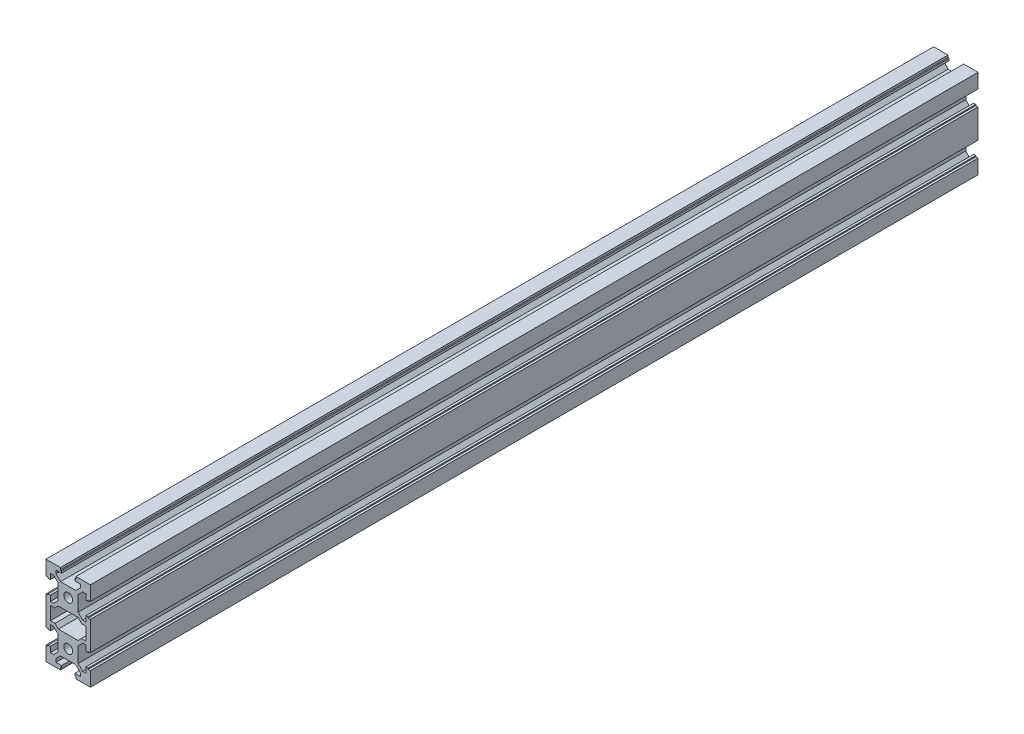
SolidWorks part; units mm, degrees
ref_plane "Front Plane" through (0, 0, 0) normal (0, 0, 1) x (1, 0, 0)
ref_plane "Top Plane" through (0, 0, 0) normal (0, 1, 0) x (1, 0, 0)
ref_plane "Right Plane" through (0, 0, 0) normal (1, 0, 0) x (0, 0, -1)
sketch "Sketch1" plane through (0, 0, 0) normal (0, 0, 1) x (1, 0, 0)
  line L0 (-10, 0) -> (10, 0) construction
  line L1 (-10, -20) -> (-3.5, -20)
  line L2 (-10, -20) -> (-10, -13.5)
  line L3 (-10, 20) -> (-3.5, 20)
  line L4 (10, -20) -> (10, -13.5)
  line L5 (-10, -20) -> (10, 20) construction
  line L6 (-10, 20) -> (10, -20) construction
  line L7 (-10, 20) -> (10, 0) construction
  line L8 (10, 20) -> (-10, 0) construction
  line L9 (-3.5, 20) -> (-3.5, 19)
  line L11 (-4.5007, 6.56) -> (-4.5007, 13.44)
  line L12 (-3.44, 14.5007) -> (3.44, 14.5007)
  line L13 (4.5007, 6.56) -> (4.5007, 13.44)
  line L14 (0, 20) -> (0, 10) construction
  line L15 (-10, 20) -> (10, 0) construction
  line L16 (-3.5, 19) -> (-3, 19)
  line L17 (-3, 19) -> (-3, 18)
  line L18 (-3, 18) -> (-5.5, 18)
  line L19 (-5.5, 18) -> (-5.5, 16.5607)
  line L20 (-5.5, 16.5607) -> (-3.44, 14.5007)
  line L21 (0, 20) -> (0, 10) construction
  line L22 (5.5, 16.5607) -> (3.44, 14.5007)
  line L23 (5.5, 18) -> (5.5, 16.5607)
  line L24 (3, 18) -> (5.5, 18)
  line L25 (3, 19) -> (3, 18)
  line L26 (3.5, 19) -> (3, 19)
  line L27 (3.5, 20) -> (3.5, 19)
  line L28 (3.5, 20) -> (10, 20)
  line L29 (-3.5, 20) -> (3.5, 20) construction
  line L30 (-9, 13.5) -> (-9, 13)
  line L31 (-6.5607, 15.5) -> (-4.5007, 13.44)
  line L32 (-8, 15.5) -> (-6.5607, 15.5)
  line L33 (-8, 13) -> (-8, 15.5)
  line L34 (-10, 13.5) -> (-9, 13.5)
  line L35 (-9, 13) -> (-8, 13)
  line L36 (10, 13.5) -> (9, 13.5)
  line L37 (9, 13.5) -> (9, 13)
  line L38 (9, 13) -> (8, 13)
  line L39 (8, 13) -> (8, 15.5)
  line L40 (8, 15.5) -> (6.5607, 15.5)
  line L41 (6.5607, 15.5) -> (4.5007, 13.44)
  line L42 (0, 10) -> (-10, 10) construction
  line L43 (10, 6.5) -> (9, 6.5)
  line L44 (9, 6.5) -> (9, 7)
  line L45 (9, 7) -> (8, 7)
  line L46 (8, 7) -> (8, 4.5)
  line L47 (8, 4.5) -> (6.5607, 4.5)
  line L48 (6.5607, 4.5) -> (4.5007, 6.56)
  line L49 (-6.5607, 4.5) -> (-4.5007, 6.56)
  line L50 (-8, 4.5) -> (-6.5607, 4.5)
  line L51 (-8, 7) -> (-8, 4.5)
  line L52 (-9, 6.5) -> (-9, 7)
  line L53 (-9, 7) -> (-8, 7)
  line L54 (-10, 6.5) -> (-9, 6.5)
  line L55 (4.5007, -6.56) -> (4.5007, -13.44)
  line L56 (-4.5007, -6.56) -> (-4.5007, -13.44)
  line L58 (-3.44, -14.5007) -> (3.44, -14.5007)
  line L59 (10, -13.5) -> (9, -13.5)
  line L60 (9, -13.5) -> (9, -13)
  line L61 (9, -13) -> (8, -13)
  line L62 (8, -13) -> (8, -15.5)
  line L63 (8, -15.5) -> (6.5607, -15.5)
  line L64 (6.5607, -15.5) -> (4.5007, -13.44)
  line L65 (6.5607, -4.5) -> (4.5007, -6.56)
  line L66 (8, -4.5) -> (6.5607, -4.5)
  line L67 (9, -6.5) -> (9, -7)
  line L68 (8, -7) -> (8, -4.5)
  line L69 (9, -7) -> (8, -7)
  line L70 (10, -6.5) -> (9, -6.5)
  line L71 (-10, -6.5) -> (-9, -6.5)
  line L72 (-8, -7) -> (-8, -4.5)
  line L73 (-6.5607, -4.5) -> (-4.5007, -6.56)
  line L74 (-8, -4.5) -> (-6.5607, -4.5)
  line L75 (-9, -7) -> (-8, -7)
  line L76 (-9, -6.5) -> (-9, -7)
  line L77 (-10, -13.5) -> (-9, -13.5)
  line L78 (-9, -13.5) -> (-9, -13)
  line L79 (-9, -13) -> (-8, -13)
  line L80 (-8, -13) -> (-8, -15.5)
  line L81 (-8, -15.5) -> (-6.5607, -15.5)
  line L82 (-6.5607, -15.5) -> (-4.5007, -13.44)
  line L83 (5.5, -16.5607) -> (3.44, -14.5007)
  line L84 (5.5, -18) -> (5.5, -16.5607)
  line L85 (3, -18) -> (5.5, -18)
  line L86 (3, -19) -> (3, -18)
  line L87 (3.5, -19) -> (3, -19)
  line L88 (3.5, -20) -> (3.5, -19)
  line L89 (-5.5, -16.5607) -> (-3.44, -14.5007)
  line L90 (-5.5, -18) -> (-5.5, -16.5607)
  line L91 (-3, -18) -> (-5.5, -18)
  line L92 (-3, -19) -> (-3, -18)
  line L93 (-3.5, -19) -> (-3, -19)
  line L94 (-3.5, -20) -> (-3.5, -19)
  line L95 (10, 13.5) -> (10, 20)
  line L96 (-10, 13.5) -> (-10, 20)
  line L97 (-10, 13.5) -> (-10, 6.5) construction
  line L98 (10, 13.5) -> (10, 6.5) construction
  line L99 (3.5, -20) -> (10, -20)
  line L100 (-10, -6.5) -> (-10, 6.5)
  line L101 (10, -6.5) -> (10, 6.5)
  line L102 (0, 0) -> (0, -20) construction
  line L103 (-3.5, -20) -> (3.5, -20) construction
  line L104 (-10, -6.5) -> (-10, -13.5) construction
  line L105 (0, -10) -> (-10, -10) construction
  line L106 (10, -6.5) -> (10, -13.5) construction
  line L107 (-4.4393, 4.5) -> (4.4393, 4.5)
  line L108 (4.4393, 4.5) -> (6.1033, 2.8361)
  line L109 (6.1033, 2.8361) -> (8, 2.8361)
  line L110 (8, 2.8361) -> (8, -2.9997)
  line L111 (8, -2.9997) -> (5.9397, -2.9997)
  line L112 (5.9397, -2.9997) -> (4.44, -4.4993)
  line L113 (4.44, -4.4993) -> (-4.44, -4.4993)
  line L114 (-4.44, -4.4993) -> (-5.9397, -2.9997)
  line L115 (-5.9397, -2.9997) -> (-8, -2.9997)
  line L116 (-8, -2.9997) -> (-8, 3.0003)
  line L117 (-8, 3.0003) -> (-5.939, 3.0003)
  line L118 (-5.939, 3.0003) -> (-4.4393, 4.5)
  circle A0 centre (0, 10) radius 2
  circle A1 centre (0, -10) radius 2
  point P0 (0, 0)
  point P8 (0, 10)
  point P10 (-9.7872, 19.7872)
  point P12 (0.1414, 20)
  point P58 (0, 0)
  point P59 (-3.3333, 6.6667)
  point P60 (0, 0)
  point P61 (10.2314, -0.0818)
  point P122 (-5.5307, -5.53)
  dimension "D17" = 4
  dimension "D18" = 4
  dimension "D1" = 40
  dimension "D2" = 20
  dimension "D3" = 0.75
  dimension "D4" = 3.5
  dimension "D5" = 3
  dimension "D6" = 1
  dimension "D7" = 1
  dimension "D8" = 5.5
  dimension "D9" = 3.44
  dimension "D10" = 1.5
  dimension "D11" = 1.5
  dimension "D12" = 1.5
  dimension "D13" = 6
  dimension "D14" = 1.5
  dimension "D15" = 1.5003
  dimension "D16" = 1.6639
extrude "Boss-Extrude1" add sketch "Sketch1" along normal blind 400
